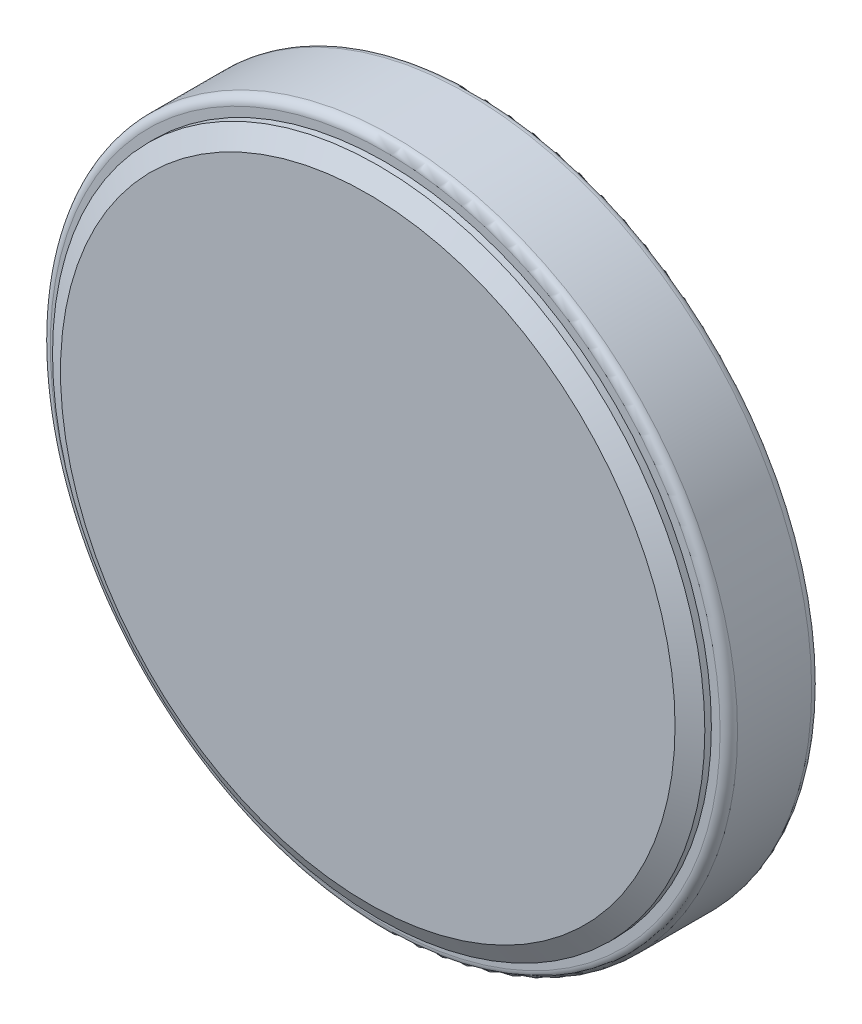
SolidWorks part; units mm, degrees
ref_plane "Plane1" through (0, 0, 0) normal (0, 0, 1) x (1, 0, 0)
ref_plane "Plane2" through (0, 0, 0) normal (0, 1, 0) x (1, 0, 0)
ref_plane "Plane3" through (0, 0, 0) normal (1, 0, 0) x (0, 0, -1)
sketch "Sketch1" plane through (0, 0, 0) normal (0, 0, 1) x (1, 0, 0)
  circle A0 centre (0, 0) radius 10.0076
extrude "Base-Extrude" add sketch "Sketch1" against normal blind 2.667
fillet "Fillet1" radius 0.254 1 edges at (10.0076, 0, -2.667)
fillet "Fillet2" radius 0.254 1 edges at (10.0076, 0, 0)
sketch "Sketch2" plane through (0, 0, 0) normal (0, 0, 1) x (1, 0, 0)
  circle A0 centre (0, 0) radius 9.4996
  circle A1 centre (0, 0) radius 9.7536
  circle A2 centre (0, 0) radius 9.7536 construction
  dimension "D1" = 0
  dimension "D2" = 0.254
extrude "Boss-Extrude2" add sketch "Sketch2" along normal offset from surface (0.508 mm away) 3.175
chamfer "Chamfer3" distance 0.3175 angle 60 1 edges at (9.4996, 0, 0.508)
sketch "Sketch3" plane through (0, 0, -2.667) normal (0, 0, -1) x (-1, 0, 0)
  line L0 (2.54, 0) -> (-2.54, 0) construction
  line L1 (-0.254, 2.54) -> (0.254, 2.54)
  line L2 (-0.254, 2.54) -> (-0.254, 0.254)
  line L3 (0, -2.54) -> (0, 2.54) construction
  line L4 (0.254, 2.54) -> (0.254, 0.254)
  line L6 (-0.254, -0.254) -> (-0.254, -2.54)
  line L7 (-0.254, -2.54) -> (0.254, -2.54)
  line L8 (0.254, -0.254) -> (0.254, -2.54)
  line L9 (0.254, 0.254) -> (2.54, 0.254)
  line L11 (0.254, -0.254) -> (2.54, -0.254)
  line L12 (2.54, 0.254) -> (2.54, -0.254)
  line L13 (-0.254, 0.254) -> (-2.54, 0.254)
  line L15 (-0.254, -0.254) -> (-2.54, -0.254)
  line L16 (-2.54, 0.254) -> (-2.54, -0.254)
  dimension "D1" = 0.508
  dimension "D2" = 5.08
  dimension "D4" = 5.08
extrude "Cut-Extrude1" cut sketch "Sketch3" against normal blind 0.254
